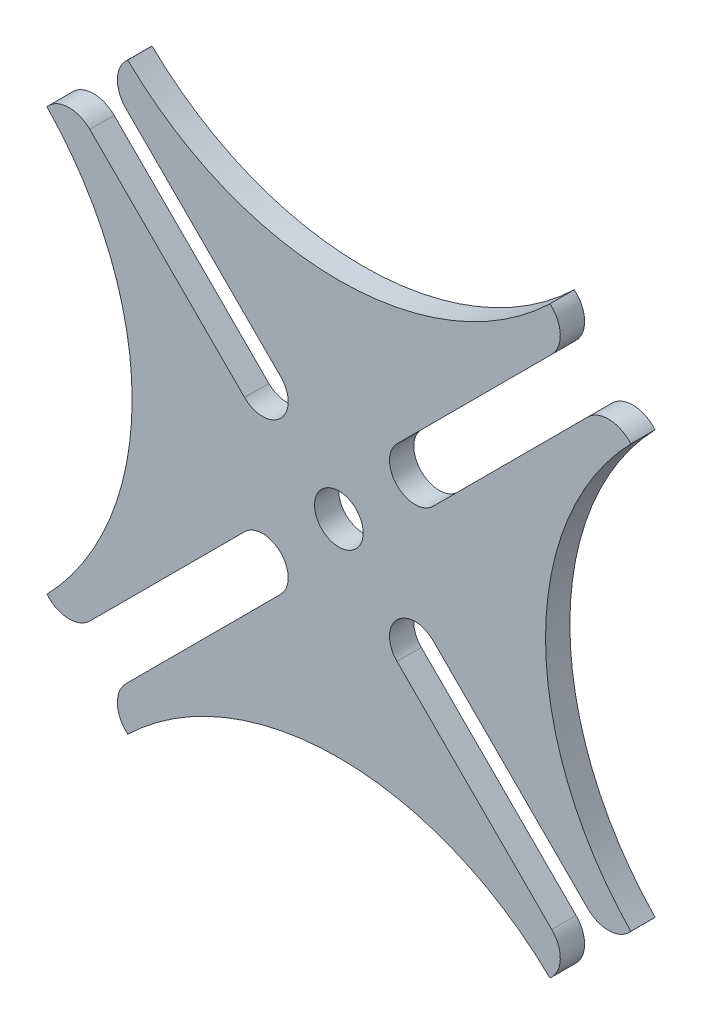
SolidWorks part; units mm, degrees
ref_plane "Přední rovina" through (0, 0, 0) normal (0, 0, 1) x (1, 0, 0)
ref_plane "Horní rovina" through (0, 0, 0) normal (0, 1, 0) x (1, 0, 0)
ref_plane "Pravá rovina" through (0, 0, 0) normal (1, 0, 0) x (0, 0, -1)
sketch "Skica1" plane through (0, 0, 0) normal (0, 0, 1) x (1, 0, 0)
  line L0 (-96.7965, 0) -> (184.88, 0) construction
  line L1 (0, 86.838) -> (0, -86.0413) construction
  line L2 (105, 82.6138) -> (105, -82.4047) construction
  line L3 (163.6997, 58.6997) -> (26.659, -78.341) construction
  line L4 (-80.0475, 80.0475) -> (88.1948, -88.1948) construction
  line L5 (67.035, 67.035) -> (-75.2521, -75.2521) construction
  line L6 (11.9542, 19.3788) -> (43.774, 51.1986)
  line L7 (19.3788, -11.9542) -> (51.1986, -43.774)
  line L8 (11.9542, -19.3788) -> (43.774, -51.1986)
  line L9 (19.3788, 11.9542) -> (51.1986, 43.774)
  line L10 (-11.9542, -19.3788) -> (-43.774, -51.1986)
  line L11 (-19.3788, -11.9542) -> (-51.1986, -43.774)
  line L12 (-19.3788, 11.9542) -> (-51.1986, 43.774)
  line L13 (-11.9542, 19.3788) -> (-43.774, 51.1986)
  arc A0 (51.1986, 43.774) -> (60.0266, 43.401) centre (55.4412, 39.5313) cw
  circle A1 centre (105, 0) radius 74.2462 construction
  circle A2 centre (0, 0) radius 30.7538 construction
  arc A3 (43.774, 51.1986) -> (43.401, 60.0266) centre (39.5313, 55.4412) ccw
  arc A4 (11.9542, 19.3788) -> (19.3788, 11.9542) centre (15.6665, 15.6665) ccw
  arc A5 (43.774, -51.1986) -> (43.401, -60.0266) centre (39.5313, -55.4412) cw
  arc A6 (43.401, -60.0266) -> (-43.401, -60.0266) centre (0, -105) ccw
  arc A7 (51.1986, -43.774) -> (60.0266, -43.401) centre (55.4412, -39.5313) ccw
  arc A8 (-51.1986, -43.774) -> (-60.0266, -43.401) centre (-55.4412, -39.5313) cw
  arc A9 (-43.774, -51.1986) -> (-43.401, -60.0266) centre (-39.5313, -55.4412) ccw
  arc A10 (60.0266, 43.401) -> (60.0266, -43.401) centre (105, 0) ccw
  arc A11 (-43.774, 51.1986) -> (-43.401, 60.0266) centre (-39.5313, 55.4412) cw
  arc A12 (-51.1986, 43.774) -> (-60.0266, 43.401) centre (-55.4412, 39.5313) ccw
  arc A13 (19.3788, -11.9542) -> (11.9542, -19.3788) centre (15.6665, -15.6665) ccw
  arc A14 (-60.0266, -43.401) -> (-60.0266, 43.401) centre (-105, 0) ccw
  arc A15 (-43.401, 60.0266) -> (43.401, 60.0266) centre (0, 105) ccw
  arc A16 (-11.9542, -19.3788) -> (-19.3788, -11.9542) centre (-15.6665, -15.6665) ccw
  arc A17 (-19.3788, 11.9542) -> (-11.9542, 19.3788) centre (-15.6665, 15.6665) ccw
  circle A18 centre (0, 0) radius 5
  dimension "D2" = 125
  dimension "D3" = 6
  dimension "D5" = 10
  dimension "D7" = 45
  dimension "D9" = 62.5
  dimension "D1" = 45
  dimension "D4" = 45
  dimension "D6" = 105
  dimension "D8" = 10.5
extrude "Přidat vysunutím1" add sketch "Skica1" along normal blind 5
